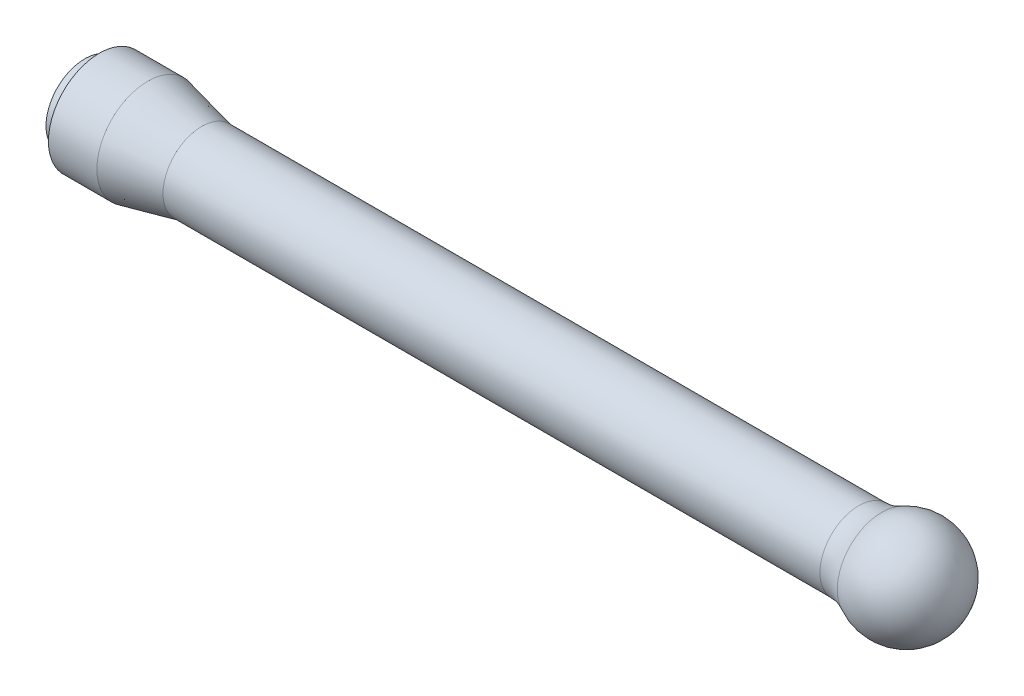
SolidWorks part; units mm, degrees
ref_plane "Plan de face" through (0, 0, 0) normal (0, 0, 1) x (1, 0, 0)
ref_plane "Plan de dessus" through (0, 0, 0) normal (0, 1, 0) x (1, 0, 0)
ref_plane "Plan de droite" through (0, 0, 0) normal (1, 0, 0) x (0, 0, -1)
sketch "Esquisse1" plane through (0, 0, 0) normal (0, 0, 1) x (1, 0, 0)
  line L0 (0, 0) -> (0, 8)
  line L1 (0, 8) -> (3, 8)
  line L2 (3, 8) -> (3, 10.5)
  line L3 (3, 10.5) -> (13, 10.5)
  line L4 (13, 10.5) -> (24.1411, 8)
  line L5 (24.1411, 8) -> (162.6993, 8)
  line L6 (-57.1322, 0) -> (63.5755, 0) construction
  line L7 (0, 0) -> (180, 0)
  arc A0 (162.6993, 8) -> (180, 0) centre (169.5, 0) cw
  point P12 (24.1411, 8)
  dimension "D7" = 10.5
  dimension "D1" = 3
  dimension "D2" = 10.5
  dimension "D3" = 8
  dimension "D4" = 180
  dimension "D5" = 10
  dimension "D6" = 8
revolve "Révolution1" add sketch "Esquisse1" angle 360 about L6
hole_wizard "Trou taraudé M2.51" positions "Esquisse3" profile "Esquisse4" tap size "M2.5" standard "ISO"
sketch "Esquisse3" plane through (0, 0, 0) normal (-1, 0, 0) x (0, 0, 1)
  point P0 (0, 5.5)
  dimension "D1" = 5.5
cosmetic thread "Filetage de perçage1" parameters "D1"=4, "D2"=2.5
sketch "Esquisse4" plane through (0, 5.5, 0) normal (0, 1, 0) x (0, 0, 1)
  line L0 (0, 0) -> (0, 5.1159)
  line L1 (0, 5.1159) -> (1.025, 4.5)
  line L2 (1.025, 4.5) -> (1.025, 0.325)
  line L3 (1.025, 0.325) -> (1.35, 0)
  line L5 (1.35, 0) -> (0, 0)
  line L6 (-1.025, 0.325) -> (-1.35, 0) construction
  line L10 (0, 5.1159) -> (-1.025, 4.5) construction
  line L11 (0, -6.35) -> (0, 107.95) construction
  dimension "Diamètre du trou pour taraudage" = 2.05
  dimension "Profondeur du trou pour taraudage" = 4.5
  dimension "Diamètre du fraisage entrant" = 2.7
  dimension "Angle du fraisage entrant" = 90
  dimension "Angle de pointe" = 118
pattern_circular "Répétition circulaire1" count 3 over 360 about axis through (0, 0, 0) along (1, 0, 0) of "Trou taraudé M2.51"
fillet "Congé1" radius 10 1 edges at (162.6993, 0, 8)
